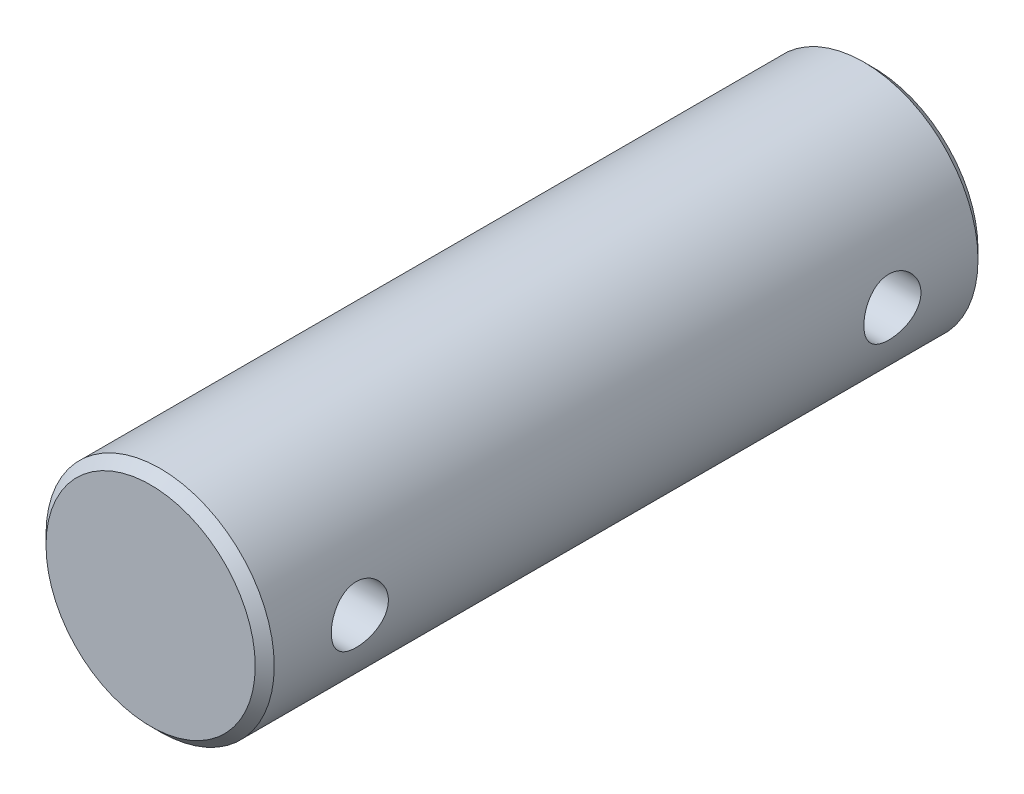
SolidWorks part; units mm, degrees
ref_plane "Front Plane" through (0, 0, 0) normal (0, 0, 1) x (1, 0, 0)
ref_plane "Top Plane" through (0, 0, 0) normal (0, 1, 0) x (1, 0, 0)
ref_plane "Right Plane" through (0, 0, 0) normal (1, 0, 0) x (0, 0, -1)
sketch "Sketch1" plane through (0, 0, 0) normal (0, 0, 1) x (1, 0, 0)
  circle A0 centre (0, 0) radius 6
  dimension "D1" = 12
extrude "Boss-Extrude1" add sketch "Sketch1" along normal mid plane 38
chamfer "Chamfer1" distance 0.5 angle 45 2 edges at (6, 0, -19) (6, 0, 19)
sketch "Sketch2" plane through (0, 0, 0) normal (1, 0, 0) x (0, 0, -1)
  line L0 (-14, 0) -> (14, 0) construction
  line L1 (-19, 5.5) -> (-19, -5.5) construction
  circle A0 centre (-14, 0) radius 1.5
  circle A1 centre (14, 0) radius 1.5
  point P4 (0, 0)
  dimension "D2" = 3
  dimension "D1" = 5
extrude "Cut-Extrude1" cut sketch "Sketch2" against normal mid plane 38
